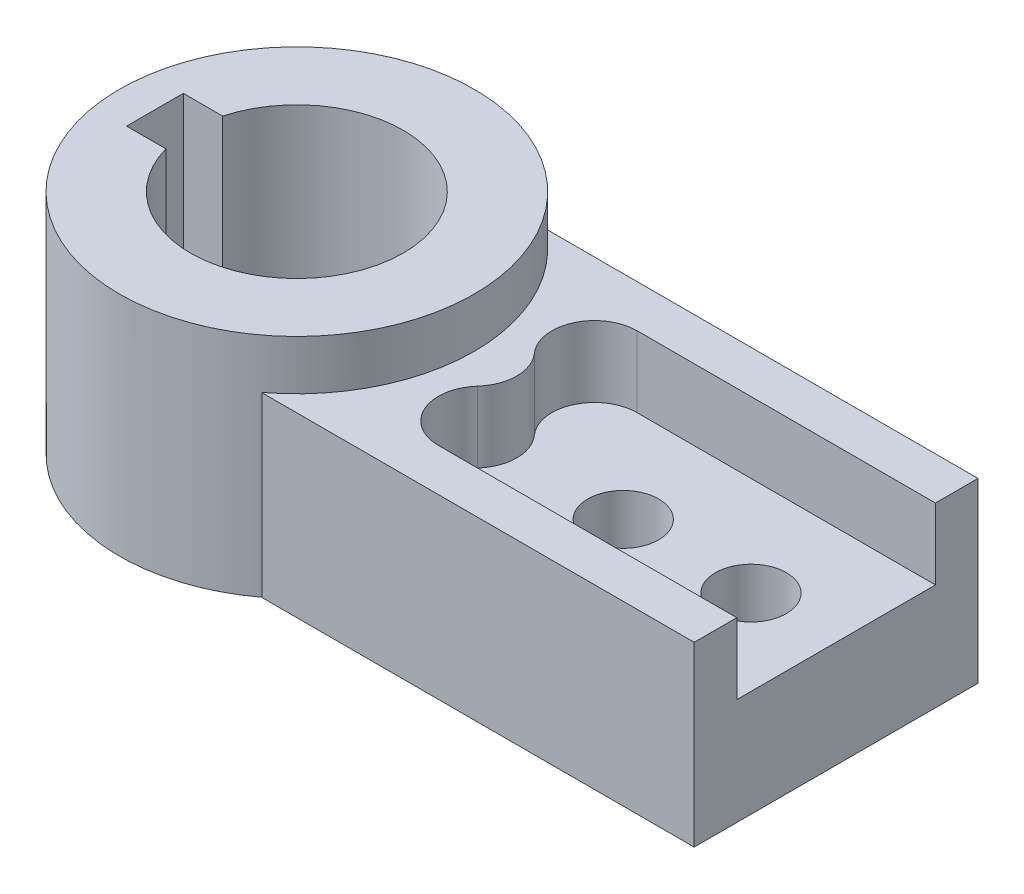
SolidWorks part; units mm, degrees
ref_plane "前视基准面" through (0, 0, 0) normal (0, 0, 1) x (1, 0, 0)
ref_plane "上视基准面" through (0, 0, 0) normal (0, 1, 0) x (1, 0, 0)
ref_plane "右视基准面" through (0, 0, 0) normal (1, 0, 0) x (0, 0, -1)
sketch "草图1" plane through (0, 0, 0) normal (0, 1, 0) x (1, 0, 0)
  circle A0 centre (0, 0) radius 25
  circle A1 centre (0, 0) radius 15
  dimension "D1" = 50
  dimension "D2" = 30
extrude "凸台-拉伸1" add sketch "草图1" along normal blind 32
sketch "草图2" plane through (0, 32, 0) normal (0, 1, 0) x (1, 0, 0)
  line L0 (0, 0) -> (61.4208, 0) construction
  line L2 (15.0746, 20) -> (76, 20)
  line L3 (15.0746, 20) -> (15.0746, -20)
  line L4 (15.0746, -20) -> (76, -20)
  line L5 (76, 20) -> (76, -20)
  line L6 (15.0746, 20) -> (76, -20) construction
  line L7 (15.0746, -20) -> (76, 20) construction
  point P3 (45.5373, 0)
  dimension "D1" = 40
  dimension "D2" = 76
extrude "凸台-拉伸2" add sketch "草图2" along normal blind 25 from offset 32 offset against normal yes
sketch "草图3" plane through (0, 25, 0) normal (0, 1, 0) x (1, 0, 0)
  line L0 (76, -20) -> (76, 20) construction
  line L1 (76, 14) -> (33.9443, 14)
  line L2 (76, 14) -> (76, -14)
  line L3 (76, -14) -> (33.9443, -14)
  line L5 (0, 0) -> (93.9798, 0) construction
  line L6 (76, 20) -> (15.0746, 20) construction
  arc A0 (33.9443, 14) -> (29.4721, 4) centre (33.9443, 8) ccw
  arc A1 (29.4721, -4) -> (33.9443, -14) centre (33.9443, -8) ccw
  arc A2 (29.4721, 4) -> (29.4721, -4) centre (25, 0) cw
  arc A4 (15.0746, -19.9439) -> (15.0746, 19.9439) centre (0, 0) ccw construction
  point P3 (31, 0)
  point P19 (25, 0)
  dimension "D2" = 6
  dimension "D1" = 6
  dimension "D3" = 6
extrude "切除-拉伸1" cut sketch "草图3" against normal blind 10
sketch "草图4" plane through (0, 15, 0) normal (0, 1, 0) x (1, 0, 0)
  line L0 (76, -14) -> (76, 14) construction
  circle A0 centre (46, 0) radius 5
  circle A1 centre (64, 0) radius 5
  dimension "D3" = 10
  dimension "D4" = 10
  dimension "D1" = 12
  dimension "D2" = 18
extrude "切除-拉伸2" cut sketch "草图4" against normal blind 48
sketch "草图5" plane through (0, 32, 0) normal (0, 1, 0) x (1, 0, 0)
  line L2 (-20, 4) -> (-14.4568, 4)
  line L3 (-20, 4) -> (-20, -4)
  line L4 (-20, -4) -> (-14.4568, -4)
  circle A0 centre (0, 0) radius 15 construction
  arc A3 (-14.4568, 4) -> (-14.4568, -4) centre (0, 0) ccw
  point P0 (0, 0)
  point P9 (15, 0)
  dimension "D1" = 8
  dimension "D2" = 35
extrude "切除-拉伸3" cut sketch "草图5" against normal blind 48
